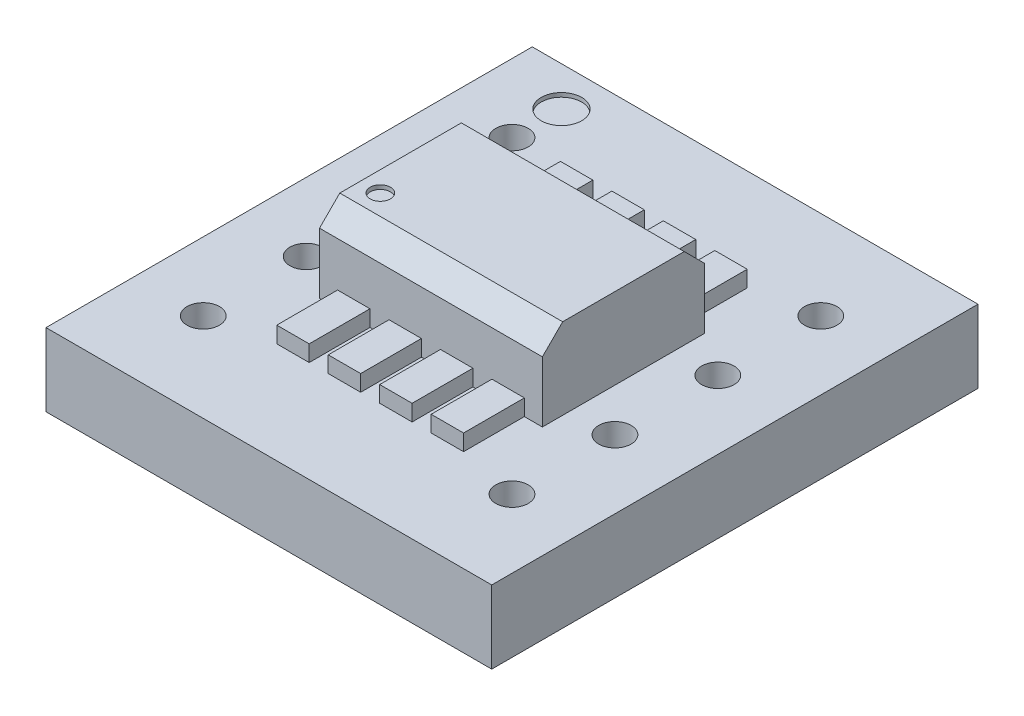
SolidWorks part; units mm, degrees
ref_plane "Front Plane" through (0, 0, 0) normal (0, 0, 1) x (1, 0, 0)
ref_plane "Top Plane" through (0, 0, 0) normal (0, 1, 0) x (1, 0, 0)
ref_plane "Right Plane" through (0, 0, 0) normal (1, 0, 0) x (0, 0, -1)
sketch "Sketch1" plane through (0, 0, 0) normal (0, 1, 0) x (1, 0, 0)
  line L1 (-5.5, -6) -> (5.5, -6)
  line L2 (-5.5, -6) -> (-5.5, 6)
  line L3 (-5.5, 6) -> (5.5, 6)
  line L4 (5.5, -6) -> (5.5, 6)
  line L5 (-5.5, -6) -> (5.5, 6) construction
  line L6 (-5.5, 6) -> (5.5, -6) construction
  point P0 (0, 0)
  dimension "D1" = 11
  dimension "D2" = 12
extrude "Boss-Extrude1" add sketch "Sketch1" along normal blind 1.8
sketch "Sketch2" plane through (0, 0, 0) normal (0, -1, 0) x (1, 0, 0)
  line L1 (-5.5, 0) -> (5.5, 0) construction
  line L2 (-5.5, -6) -> (-5.5, 6) construction
  line L3 (5.5, 6) -> (5.5, -6) construction
  line L4 (-2.54, 5.08) -> (2.54, 5.08) construction
  line L5 (-5.08, -5.08) -> (-2.54, -5.08)
  line L6 (-5.08, -5.08) -> (-5.08, 5.08)
  line L7 (-5.08, 5.08) -> (-2.54, 5.08)
  line L8 (-2.54, -5.08) -> (-2.54, 5.08)
  line L9 (-5.08, -5.08) -> (-2.54, 5.08) construction
  line L10 (-5.08, 5.08) -> (-2.54, -5.08) construction
  line L11 (2.54, -5.08) -> (5.08, -5.08)
  line L12 (2.54, -5.08) -> (2.54, 5.08)
  line L13 (2.54, 5.08) -> (5.08, 5.08)
  line L14 (5.08, -5.08) -> (5.08, 5.08)
  line L15 (2.54, -5.08) -> (5.08, 5.08) construction
  line L16 (2.54, 5.08) -> (5.08, -5.08) construction
  line L17 (0, 5.08) -> (0, 0) construction
  point P0 (-3.81, 0)
  point P11 (3.81, 0)
  dimension "D1" = 2.54
  dimension "D2" = 10.16
  dimension "D3" = 10.16
extrude "Boss-Extrude2" add sketch "Sketch2" along normal blind 2.54
sketch "Sketch3" plane through (0, -2.54, 0) normal (0, -1, 0) x (1, 0, 0)
  line L0 (3.81, 5.08) -> (3.81, -5.08) construction
  line L1 (5.08, 5.08) -> (2.54, 5.08) construction
  line L2 (2.54, -5.08) -> (5.08, -5.08) construction
  line L3 (3.56, 1.52) -> (4.06, 1.52)
  line L4 (3.56, 4.06) -> (4.06, 4.06)
  line L5 (3.56, 4.06) -> (3.56, 3.56)
  line L6 (3.56, 3.56) -> (4.06, 3.56)
  line L7 (4.06, 4.06) -> (4.06, 3.56)
  line L8 (3.56, 4.06) -> (4.06, 3.56) construction
  line L9 (3.56, 3.56) -> (4.06, 4.06) construction
  line L10 (4.06, 1.52) -> (4.06, 1.02)
  line L11 (3.56, 1.02) -> (4.06, 1.02)
  line L12 (3.56, 1.52) -> (3.56, 1.02)
  line L13 (3.56, 1.02) -> (4.06, 1.52) construction
  line L14 (3.56, 1.52) -> (4.06, 1.02) construction
  line L15 (3.56, -1.02) -> (4.06, -1.02)
  line L16 (4.06, -1.02) -> (4.06, -1.52)
  line L17 (3.56, -1.52) -> (4.06, -1.52)
  line L18 (3.56, -1.02) -> (3.56, -1.52)
  line L19 (3.56, -1.52) -> (4.06, -1.02) construction
  line L20 (3.56, -1.02) -> (4.06, -1.52) construction
  line L21 (3.56, -3.56) -> (4.06, -3.56)
  line L22 (4.06, -3.56) -> (4.06, -4.06)
  line L23 (3.56, -4.06) -> (4.06, -4.06)
  line L24 (3.56, -3.56) -> (3.56, -4.06)
  line L25 (3.56, -4.06) -> (4.06, -3.56) construction
  line L26 (3.56, -3.56) -> (4.06, -4.06) construction
  line L27 (3.56, 4.06) -> (3.56, 5.08) construction
  line L28 (5.08, 5.08) -> (2.54, 5.08) construction
  line L29 (3.56, -4.06) -> (3.56, -5.08) construction
  point P6 (3.81, 3.81)
  dimension "D2" = 0.5
  dimension "D3" = 2.54
  dimension "D1" = 4
extrude "Boss-Extrude3" add sketch "Sketch3" along normal blind 6.5 and the other way offset from surface (5.84 mm away) 1.5 other way up to face at (0, 1.8, 0)
mirror "Mirror1" about plane through (0, 0, 0) normal (1, 0, 0) of "Boss-Extrude3"
sketch "Sketch4" plane through (0, 1.8, 0) normal (0, 1, 0) x (1, 0, 0)
  line L1 (-2.75, -2) -> (2.75, -2)
  line L2 (-2.75, -2) -> (-2.75, 2)
  line L3 (-2.75, 2) -> (2.75, 2)
  line L4 (2.75, -2) -> (2.75, 2)
  line L5 (-2.75, -2) -> (2.75, 2) construction
  line L6 (-2.75, 2) -> (2.75, -2) construction
  point P0 (0, 0)
  dimension "D1" = 4
  dimension "D2" = 5.5
extrude "Boss-Extrude4" add sketch "Sketch4" along normal blind 2
chamfer "Chamfer1" distance 0.5 angle 45 2 edges at (0, 3.8, -2) (0, 3.8, 2)
sketch "Sketch5" plane through (0, 1.8, 0) normal (0, 1, 0) x (1, 0, 0)
  line L0 (-2.75, 0) -> (2.75, 0) construction
  line L1 (-2.75, 2) -> (-2.75, -2) construction
  line L2 (2.75, -1.5) -> (2.75, 1.5) construction
  line L3 (-0.235, -3.5) -> (-0.235, 3.5)
  line L4 (-2.305, -3.5) -> (-1.505, -3.5)
  line L5 (-2.305, -3.5) -> (-2.305, 3.5)
  line L6 (-2.305, 3.5) -> (-1.505, 3.5)
  line L7 (-1.505, -3.5) -> (-1.505, 3.5)
  line L8 (-2.305, -3.5) -> (-1.505, 3.5) construction
  line L9 (-2.305, 3.5) -> (-1.505, -3.5) construction
  line L10 (-1.035, 3.5) -> (-0.235, 3.5)
  line L11 (-1.035, -3.5) -> (-1.035, 3.5)
  line L12 (-1.035, -3.5) -> (-0.235, -3.5)
  line L13 (-1.035, -3.5) -> (-0.235, 3.5) construction
  line L14 (-1.035, 3.5) -> (-0.235, -3.5) construction
  line L15 (1.035, -3.5) -> (1.035, 3.5)
  line L16 (0.235, 3.5) -> (1.035, 3.5)
  line L17 (0.235, -3.5) -> (0.235, 3.5)
  line L18 (0.235, -3.5) -> (1.035, -3.5)
  line L19 (0.235, -3.5) -> (1.035, 3.5) construction
  line L20 (0.235, 3.5) -> (1.035, -3.5) construction
  line L21 (2.305, -3.5) -> (2.305, 3.5)
  line L22 (1.505, 3.5) -> (2.305, 3.5)
  line L23 (1.505, -3.5) -> (1.505, 3.5)
  line L24 (1.505, -3.5) -> (2.305, -3.5)
  line L25 (1.505, -3.5) -> (2.305, 3.5) construction
  line L26 (1.505, 3.5) -> (2.305, -3.5) construction
  line L27 (-2.305, 3.5) -> (-2.75, 2) construction
  line L28 (2.305, 3.5) -> (2.75, 2) construction
  line L29 (2.75, 2) -> (-2.75, 2) construction
  point P6 (-1.905, 0)
  dimension "D1" = 0.8
  dimension "D3" = 1.27
  dimension "D4" = 1.5
  dimension "D2" = 4
extrude "Boss-Extrude5" add sketch "Sketch5" along normal blind 0.4
sketch "Sketch6" plane through (0, 1.8, 0) normal (0, 1, 0) x (1, 0, 0)
  line L0 (-3.81, 4.06) -> (-3.81, 6) construction
  line L1 (-4.06, 4.06) -> (-3.56, 4.06) construction
  line L2 (5.5, 6) -> (-5.5, 6) construction
  circle A0 centre (-3.81, 5.03) radius 0.5
  point P9 (-3.81, 5.03)
  dimension "D1" = 1
extrude "Cut-Extrude1" cut sketch "Sketch6" against normal blind 0.1
sketch "Sketch7" plane through (0, 3.8, 0) normal (0, 1, 0) x (1, 0, 0)
  line L0 (-2.75, 2) -> (-2.75, -2) construction
  line L1 (-2.75, -1.5) -> (2.75, -1.5) construction
  circle A0 centre (-2.25, -1) radius 0.25
  dimension "D1" = 0.5
  dimension "D2" = 0.5
  dimension "D3" = 0.5
extrude "Cut-Extrude2" cut sketch "Sketch7" against normal blind 0.1
sketch "Sketch8" plane through (0, 3.8, 0) normal (0, 1, 0) x (1, 0, 0)
  circle A0 centre (0, 0) radius 1
  dimension "D1" = 2
sketch "Sketch9" plane through (0, 0, 0) normal (0, -1, 0) x (1, 0, 0)
  line L5 (5.5, -6) -> (5.5, 6)
  line L6 (5.5, 6) -> (-5.5, 6)
  line L7 (-5.5, 6) -> (-5.5, -6)
  line L8 (-5.5, -6) -> (5.5, -6)
  line L9 (5.5, -6) -> (5.5, 6)
  line L10 (5.5, 6) -> (-5.5, 6)
  line L11 (-5.5, 6) -> (-5.5, -6)
  line L12 (-5.5, -6) -> (5.5, -6)
  dimension "D1" = 0
extrude "Cut-Extrude3" cut sketch "Sketch9" along normal blind 31
sketch "Sketch10" plane through (0, 1.8, 0) normal (0, 1, 0) x (1, 0, 0)
  line L0 (-3.81, 4.06) -> (-3.81, -4.06) construction
  line L1 (-4.06, 4.06) -> (-3.56, 4.06) construction
  line L2 (-4.06, -4.06) -> (-3.56, -4.06) construction
  line L3 (-4.06, -3.81) -> (-3.81, -3.81) construction
  line L4 (-4.06, -3.56) -> (-4.06, -4.06) construction
  line L5 (-4.06, -1.27) -> (-3.81, -1.27) construction
  line L6 (-4.06, -1.02) -> (-4.06, -1.52) construction
  line L7 (-4.06, 1.27) -> (-3.81, 1.27) construction
  line L8 (-4.06, 1.02) -> (-4.06, 1.52) construction
  line L9 (-4.06, 3.81) -> (-3.81, 3.81) construction
  line L10 (-4.06, 3.56) -> (-4.06, 4.06) construction
  line L11 (0, 6) -> (0, 4.5878) construction
  line L12 (5.5, 6) -> (-5.5, 6) construction
  circle A0 centre (-3.81, -3.81) radius 0.4
  circle A1 centre (-3.81, -1.27) radius 0.4
  circle A2 centre (-3.81, 1.27) radius 0.4
  circle A3 centre (-3.81, 3.81) radius 0.4
  circle A4 centre (3.81, -3.81) radius 0.4
  circle A5 centre (3.81, -1.27) radius 0.4
  circle A6 centre (3.81, 1.27) radius 0.4
  circle A7 centre (3.81, 3.81) radius 0.4
  dimension "D1" = 0.8
extrude "Cut-Extrude4" cut sketch "Sketch10" against normal through all both and the other way through all
